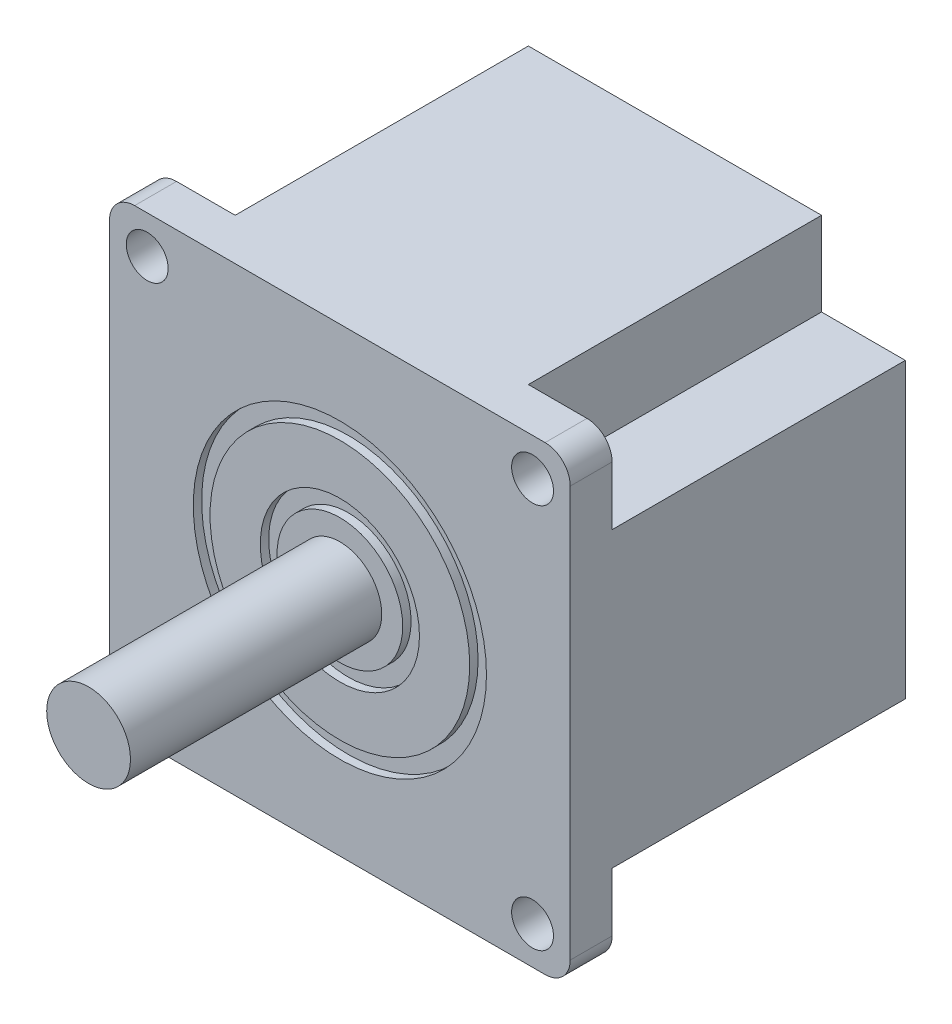
SolidWorks part; units mm, degrees
material "PA Type 6"
ref_plane "Front Plane" through (0, 0, 0) normal (0, 0, 1) x (1, 0, 0)
ref_plane "Top Plane" through (0, 0, 0) normal (0, 1, 0) x (1, 0, 0)
ref_plane "Right Plane" through (0, 0, 0) normal (1, 0, 0) x (0, 0, -1)
sketch "Sketch1" plane through (0, 0, 0) normal (0, 0, 1) x (1, 0, 0)
  line L0 (-27.5, -17.5) -> (-27.5, 17.5)
  line L1 (-17.5, -27.5) -> (17.5, -27.5)
  line L2 (-17.5, 27.5) -> (17.5, 27.5)
  line L3 (27.5, -17.5) -> (27.5, 17.5)
  line L4 (0, 27.5) -> (0, -27.5) construction
  line L5 (-27.5, 0) -> (27.5, 0) construction
  line L10 (-17.5, 27.5) -> (-17.5, 17.5)
  line L11 (-17.5, 17.5) -> (-27.5, 17.5)
  line L12 (17.5, 27.5) -> (17.5, 17.5)
  line L13 (17.5, 17.5) -> (27.5, 17.5)
  line L14 (-17.5, -17.5) -> (-27.5, -17.5)
  line L15 (-17.5, -27.5) -> (-17.5, -17.5)
  line L16 (17.5, -27.5) -> (17.5, -17.5)
  line L17 (17.5, -17.5) -> (27.5, -17.5)
  point P1 (0, 0)
  point P14 (0, 0)
  dimension "D1" = 55
  dimension "D2" = 10
extrude "Boss-Extrude1" add sketch "Sketch1" along normal blind 40
sketch "Sketch3" plane through (0, 0, 40) normal (0, 0, 1) x (1, 0, 0)
  line L0 (0, 27.5) -> (0, -27.5) construction
  line L1 (27.5, 0) -> (-27.5, 0) construction
  line L12 (-17.5, 27.5) -> (-17.5, 17.5)
  line L13 (-17.5, 17.5) -> (-27.5, 17.5)
  line L14 (-27.5, 17.5) -> (-27.5, -17.5)
  line L15 (-27.5, -17.5) -> (-17.5, -17.5)
  line L16 (-17.5, -17.5) -> (-17.5, -27.5)
  line L17 (-17.5, -27.5) -> (17.5, -27.5)
  line L18 (17.5, -27.5) -> (17.5, -17.5)
  line L19 (17.5, -17.5) -> (27.5, -17.5)
  line L20 (27.5, -17.5) -> (27.5, 17.5)
  line L21 (27.5, 17.5) -> (17.5, 17.5)
  line L22 (17.5, 17.5) -> (17.5, 27.5)
  line L23 (17.5, 27.5) -> (-17.5, 27.5)
  line L24 (-17.5, 27.5) -> (-17.5, 17.5)
  line L25 (-17.5, 17.5) -> (-27.5, 17.5)
  line L26 (-27.5, 24.5) -> (-27.5, -24.5)
  line L27 (-27.5, -17.5) -> (-17.5, -17.5)
  line L28 (-17.5, -17.5) -> (-17.5, -27.5)
  line L29 (-24.5, -27.5) -> (24.5, -27.5)
  line L30 (17.5, -27.5) -> (17.5, -17.5)
  line L31 (17.5, -17.5) -> (27.5, -17.5)
  line L32 (27.5, -24.5) -> (27.5, 24.5)
  line L33 (27.5, 17.5) -> (17.5, 17.5)
  line L34 (17.5, 17.5) -> (17.5, 27.5)
  line L35 (24.5, 27.5) -> (-24.5, 27.5)
  arc A0 (-27.5, 24.5) -> (-24.5, 27.5) centre (-24.5, 24.5) cw
  arc A1 (-27.5, -24.5) -> (-24.5, -27.5) centre (-24.5, -24.5) ccw
  arc A2 (27.5, -24.5) -> (24.5, -27.5) centre (24.5, -24.5) cw
  arc A3 (24.5, 27.5) -> (27.5, 24.5) centre (24.5, 24.5) cw
  circle A4 centre (-23, 23) radius 2.5
  circle A5 centre (23, 23) radius 2.5
  circle A6 centre (23, -23) radius 2.5
  circle A7 centre (-23, -23) radius 2.5
  line M19 (-17.5, 27.5) -> (-17.5, 17.5)
  line M20 (-17.5, 17.5) -> (-27.5, 17.5)
  line M21 (-27.5, 17.5) -> (-27.5, -17.5)
  line M22 (-27.5, -17.5) -> (-17.5, -17.5)
  line M23 (-17.5, -17.5) -> (-17.5, -27.5)
  line M24 (-17.5, -27.5) -> (17.5, -27.5)
  line M25 (17.5, -27.5) -> (17.5, -17.5)
  line M26 (17.5, -17.5) -> (27.5, -17.5)
  line M27 (27.5, -17.5) -> (27.5, 17.5)
  line M28 (27.5, 17.5) -> (17.5, 17.5)
  line M29 (17.5, 17.5) -> (17.5, 27.5)
  line M30 (17.5, 27.5) -> (-17.5, 27.5)
  dimension "D2" = 3
  dimension "D4" = 5
  dimension "D3" = 4.5
  dimension "D5" = 4.5
  dimension "D1" = 0
extrude "Boss-Extrude2" add sketch "Sketch3" against normal blind 5 contours M30 M19 M20 M21 M22 M23 M24 M25 M26 M27 M28 M29 | A3 L35 L32 A5 M29 M28 | A2 L32 L29 A6 M26 M25 | L26 A1 L29 A7 M23 M22 | A0 L26 L35 A4 M20 M19
sketch "Sketch4" plane through (0, 0, 40) normal (0, 0, 1) x (1, 0, 0)
  line L0 (0, 27.5) -> (0, -27.5)
  line L4 (24.5, 27.5) -> (-24.5, 27.5)
  line L5 (-27.5, 24.5) -> (-27.5, -24.5)
  line L6 (-24.5, -27.5) -> (24.5, -27.5)
  line L7 (27.5, -24.5) -> (27.5, 24.5)
  line L8 (24.5, 27.5) -> (-24.5, 27.5)
  line L9 (-27.5, 24.5) -> (-27.5, -24.5)
  line L10 (-24.5, -27.5) -> (24.5, -27.5)
  line L11 (27.5, -24.5) -> (27.5, 24.5)
  circle A0 centre (0, 0) radius 5
  arc A4 (-24.5, 27.5) -> (-27.5, 24.5) centre (-24.5, 24.5) ccw
  arc A5 (-27.5, -24.5) -> (-24.5, -27.5) centre (-24.5, -24.5) ccw
  arc A6 (24.5, -27.5) -> (27.5, -24.5) centre (24.5, -24.5) ccw
  arc A7 (27.5, 24.5) -> (24.5, 27.5) centre (24.5, 24.5) ccw
  arc A8 (-24.5, 27.5) -> (-27.5, 24.5) centre (-24.5, 24.5) ccw
  arc A9 (-27.5, -24.5) -> (-24.5, -27.5) centre (-24.5, -24.5) ccw
  arc A10 (24.5, -27.5) -> (27.5, -24.5) centre (24.5, -24.5) ccw
  arc A11 (27.5, 24.5) -> (24.5, 27.5) centre (24.5, 24.5) ccw
  dimension "D2" = 10
  dimension "D1" = 0
extrude "Boss-Extrude3" add sketch "Sketch4" along normal blind 30 contours L0 A0 | L0 A0
sketch "Sketch5" plane through (0, 0, 40) normal (0, 0, 1) x (1, 0, 0)
  circle A0 centre (0, 0) radius 7.5
  circle A1 centre (0, 0) radius 9.5
  circle A2 centre (0, 0) radius 15.5
  circle A3 centre (0, 0) radius 17.5
  dimension "D1" = 15
  dimension "D2" = 2
  dimension "D3" = 6
  dimension "D4" = 2
extrude "Cut-Extrude1" cut sketch "Sketch5" against normal blind 1 contours A1 A0 | A3 A2
